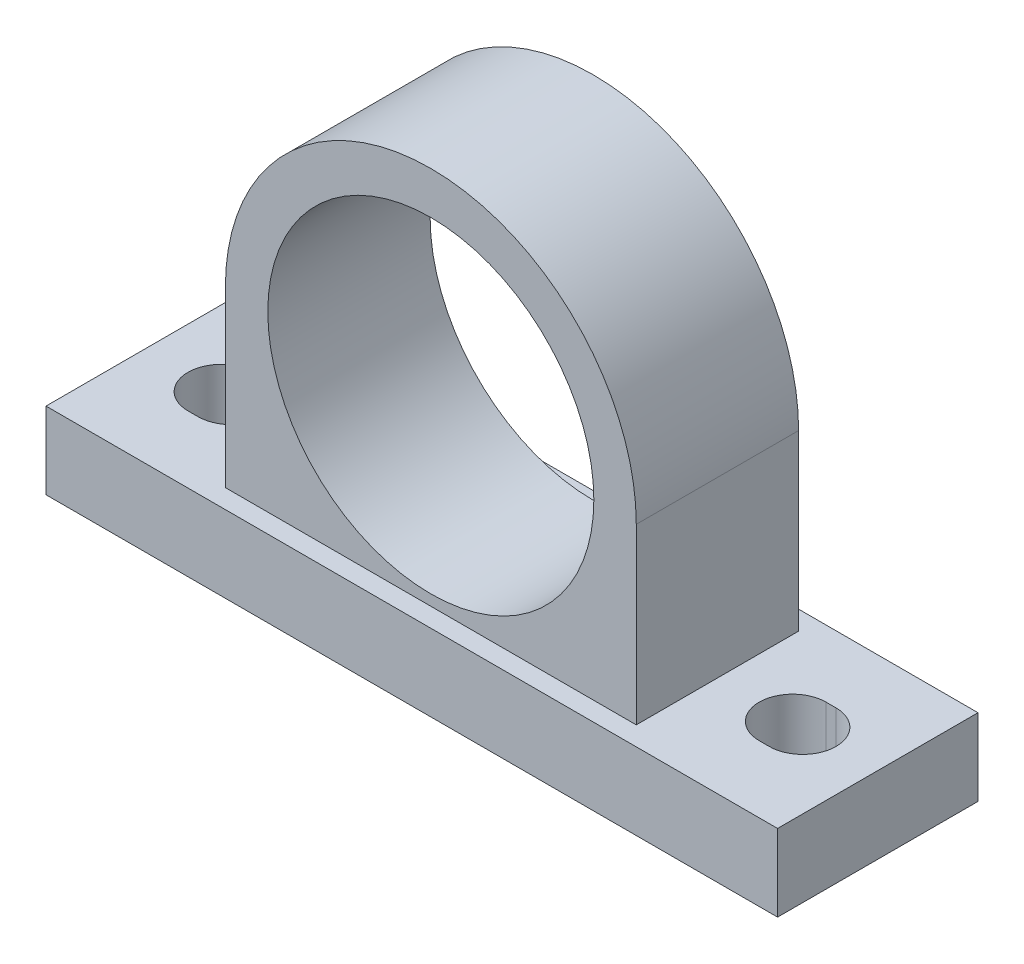
SolidWorks part; units mm, degrees
ref_plane "Front Plane" through (0, 0, 0) normal (0, 0, 1) x (1, 0, 0)
ref_plane "Top Plane" through (0, 0, 0) normal (0, 1, 0) x (1, 0, 0)
ref_plane "Right Plane" through (0, 0, 0) normal (1, 0, 0) x (0, 0, -1)
sketch "Sketch1" plane through (0, 0, 0) normal (0, 1, 0) x (1, 0, 0)
  line L0 (-96.7127, 0) -> (96.7127, 0) construction
  line L1 (0, -83.4214) -> (0, 83.4214) construction
  line L3 (-109.4994, -29.9999) -> (109.4994, -29.9999)
  line L4 (-109.4994, -29.9999) -> (-109.4994, 29.9999)
  line L5 (-109.4994, 29.9999) -> (109.4994, 29.9999)
  line L6 (109.4994, -29.9999) -> (109.4994, 29.9999)
  line L7 (-109.4994, -29.9999) -> (109.4994, 29.9999) construction
  line L8 (-109.4994, 29.9999) -> (109.4994, -29.9999) construction
  point P0 (0, 0)
  point P4 (0, 0)
  point P8 (0, 0)
  dimension "D1" = 218.9988
  dimension "D2" = 59.9999
extrude "Boss-Extrude1" add sketch "Sketch1" along normal mid plane 22.9997
sketch "Sketch2" plane through (0, 11.4998, 0) normal (0, 1, 0) x (1, 0, 0)
  line L0 (-141.5377, 0) -> (141.5377, 0) construction
  line L1 (0, -72.4807) -> (0, 72.4807) construction
  line L2 (-87.0014, 0) -> (-84.0016, 0) construction
  line L3 (-87.0014, 10) -> (-84.0016, 10)
  line L4 (-87.0014, -10) -> (-84.0016, -10)
  line L5 (87.0014, 0) -> (84.0016, 0) construction
  line L6 (87.0013, 10) -> (84.0016, 10)
  line L7 (87.0014, -10) -> (84.0016, -10)
  arc A1 (-87.0014, 10) -> (-87.0014, -10) centre (-87.0014, 0) ccw
  arc A2 (-84.0016, -10) -> (-84.0016, 10) centre (-84.0016, 0) ccw
  arc A3 (87.0013, 10) -> (87.0014, -10) centre (87.0014, 0) cw
  arc A4 (84.0016, -10) -> (84.0016, 10) centre (84.0016, 0) cw
  point P4 (0, 0)
  point P8 (0, 0)
  point P10 (-85.5015, 0)
  point P16 (85.5015, 0)
  dimension "D1" = 10
  dimension "D2" = 2.9997
  dimension "D3" = 85.5015
extrude "Cut-Extrude1" cut sketch "Sketch2" against normal blind 22.9997
sketch "Sketch3" plane through (0, 0, 0) normal (0, 0, 1) x (1, 0, 0)
  line L0 (-170.0762, 0) -> (170.0762, 0) construction
  line L1 (0, -105.0867) -> (0, 105.0867) construction
  line L2 (-117.2815, 125.001) -> (117.2815, 125.001) construction
  line L3 (-107.3498, 63.5) -> (107.3498, 63.5) construction
  line L4 (-85.5015, -161.8259) -> (-85.5015, 161.8259) construction
  line L5 (85.5015, -157.7351) -> (85.5015, 157.7351) construction
  line L6 (-74.0016, -149.5535) -> (-74.0016, 149.5535) construction
  line L7 (74.0016, -149.5535) -> (74.0016, 149.5535) construction
  line L8 (-61.501, 63.5) -> (-61.501, 11.4998)
  line L9 (-109.4994, 11.4998) -> (109.4994, 11.4998) construction
  line L10 (61.501, 63.5) -> (61.501, 11.4998)
  line L11 (-61.501, 11.4998) -> (61.501, 11.4998)
  circle A0 centre (0, 63.5) radius 25.4 construction
  arc A1 (61.501, 63.5) -> (-61.501, 63.5) centre (0, 63.5) ccw
  circle A2 centre (0, 63.5) radius 48.801
  point P4 (0, 0)
  point P8 (0, 0)
  point P11 (0, 125.001)
  point P14 (0, 63.5)
  point P20 (-85.5015, 0)
  point P23 (85.5015, 0)
  point P26 (-74.0016, 0)
  dimension "D3" = 50.8
  dimension "D4" = 85.5015
  dimension "D7" = 12.7
  dimension "D8" = 97.602
  dimension "D1" = 125.001
  dimension "D2" = 63.5
  dimension "D5" = 85.5015
  dimension "D6" = 11.4998
extrude "Boss-Extrude2" add sketch "Sketch3" along normal mid plane 48.6004
